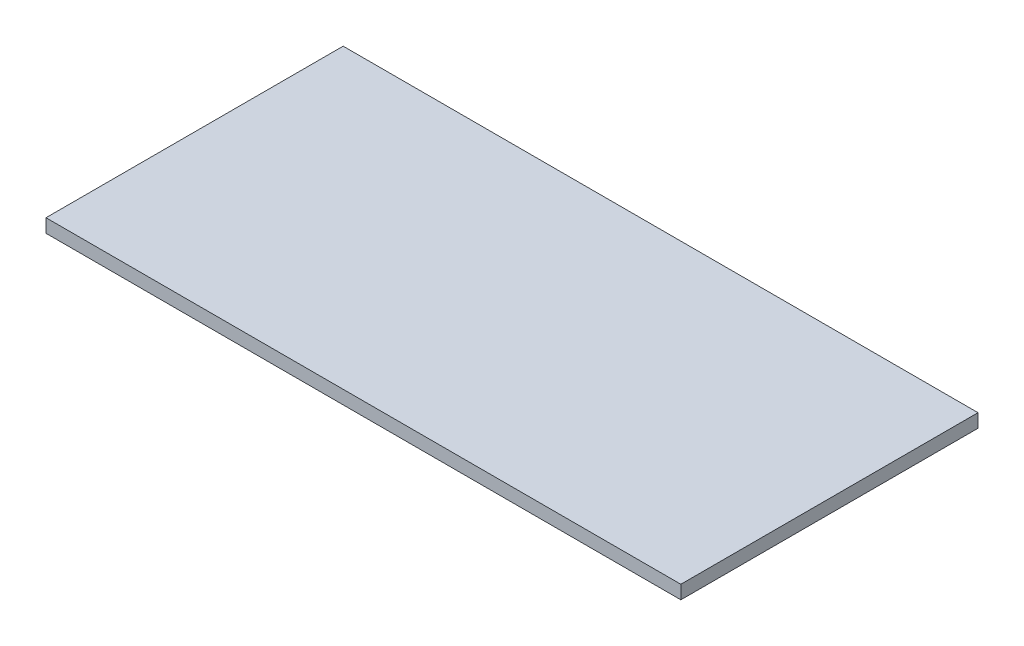
SolidWorks part; units mm, degrees
ref_plane "Front Plane" through (0, 0, 0) normal (0, 0, 1) x (1, 0, 0)
ref_plane "Top Plane" through (0, 0, 0) normal (0, 1, 0) x (1, 0, 0)
ref_plane "Right Plane" through (0, 0, 0) normal (1, 0, 0) x (0, 0, -1)
sketch "Sketch1" plane through (0, 0, 0) normal (0, 1, 0) x (1, 0, 0)
  line L1 (-70.5, -33) -> (70.5, -33)
  line L2 (-70.5, -33) -> (-70.5, 33)
  line L3 (-70.5, 33) -> (70.5, 33)
  line L4 (70.5, -33) -> (70.5, 33)
  line L5 (-70.5, -33) -> (70.5, 33) construction
  line L6 (-70.5, 33) -> (70.5, -33) construction
  point P0 (0, 0)
  dimension "D1" = 141
  dimension "D2" = 66
extrude "Boss-Extrude1" add sketch "Sketch1" along normal blind 3
